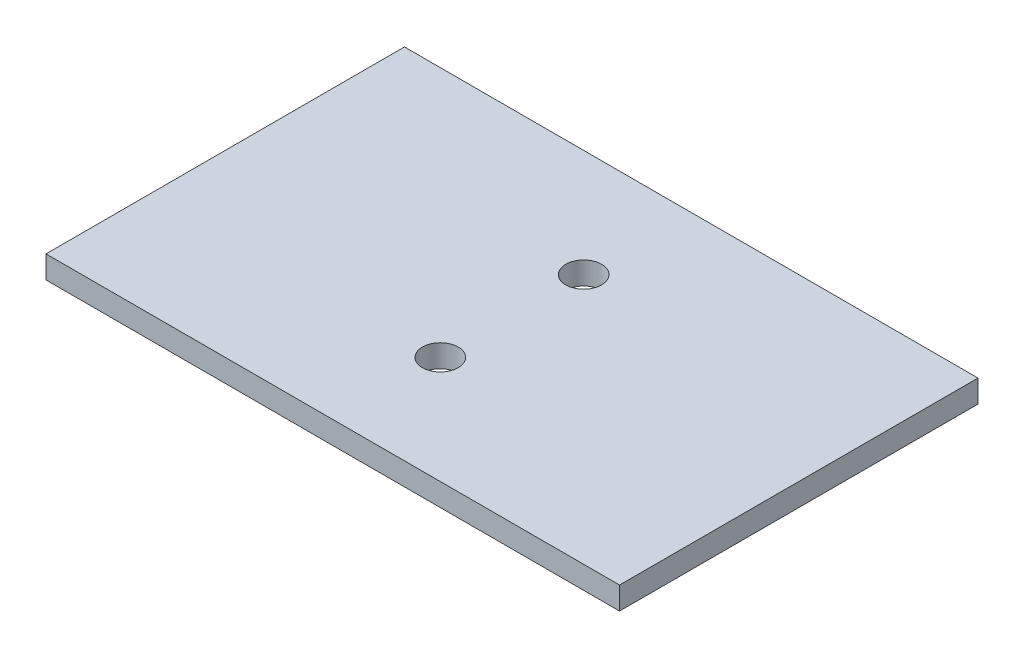
SolidWorks part; units mm, degrees
ref_plane "Front Plane" through (0, 0, 0) normal (0, 0, 1) x (1, 0, 0)
ref_plane "Top Plane" through (0, 0, 0) normal (0, 1, 0) x (1, 0, 0)
ref_plane "Right Plane" through (0, 0, 0) normal (1, 0, 0) x (0, 0, -1)
sketch "Sketch1" plane through (0, 0, 0) normal (0, 1, 0) x (1, 0, 0)
  line L0 (0, 6.35) -> (0, -6.35) construction
  line L1 (-25.4, -15.875) -> (25.4, -15.875)
  line L2 (-25.4, -15.875) -> (-25.4, 15.875)
  line L3 (-25.4, 15.875) -> (25.4, 15.875)
  line L4 (25.4, -15.875) -> (25.4, 15.875)
  line L5 (-25.4, -15.875) -> (25.4, 15.875) construction
  line L6 (-25.4, 15.875) -> (25.4, -15.875) construction
  circle A0 centre (0, 6.35) radius 1.5875
  circle A1 centre (0, -6.35) radius 1.5875
  point P0 (0, 0)
  point P10 (0, 0)
  dimension "D4" = 3.175
  dimension "D1" = 50.8
  dimension "D2" = 31.75
  dimension "D3" = 12.7
extrude "Boss-Extrude1" add sketch "Sketch1" along normal blind 2
